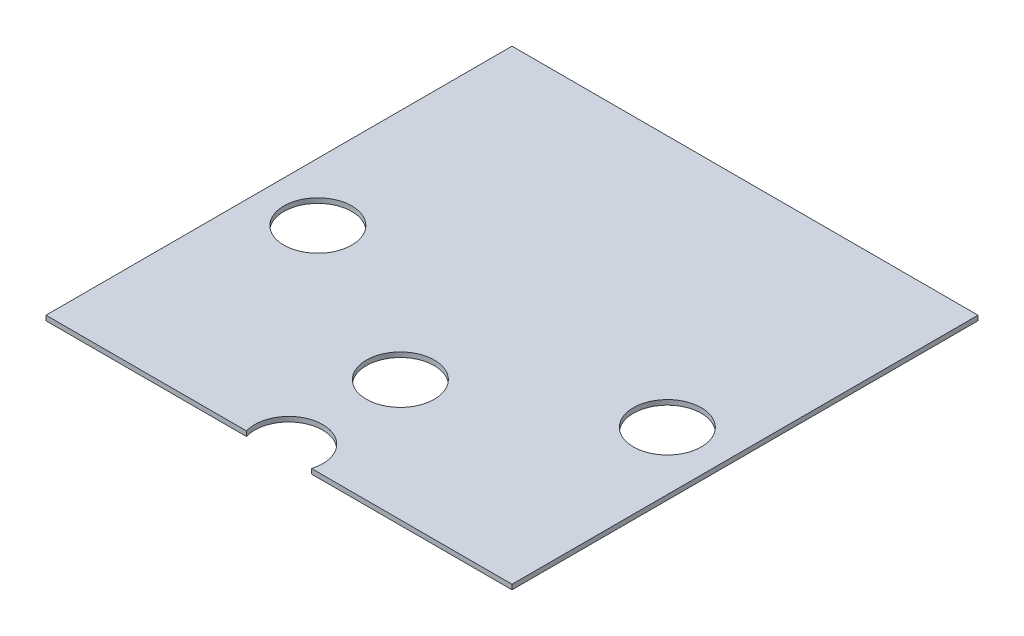
SolidWorks part; units mm, degrees
ref_plane "Front Plane" through (0, 0, 0) normal (0, 0, 1) x (1, 0, 0)
ref_plane "Top Plane" through (0, 0, 0) normal (0, 1, 0) x (1, 0, 0)
ref_plane "Right Plane" through (0, 0, 0) normal (1, 0, 0) x (0, 0, -1)
sketch "Sketch1" plane through (0, 0, 0) normal (0, 1, 0) x (1, 0, 0)
  line L1 (-387.1576, 281.7091) -> (222.4424, 281.7091)
  line L2 (-387.1576, 281.7091) -> (-387.1576, -327.8909)
  line L3 (-387.1576, -327.8909) -> (222.4424, -327.8909)
  line L4 (222.4424, 281.7091) -> (222.4424, -327.8909)
  dimension "D1" = 609.6
  dimension "D2" = 609.6
extrude "Boss-Extrude1" add sketch "Sketch1" along normal blind 6.35
sketch "Sketch2" plane through (0, 6.35, 0) normal (0, 1, 0) x (1, 0, 0)
  line L12 (82.7424, -547.9486) -> (82.7424, -311.0332)
  line L14 (89.0924, -549.9737) -> (89.0924, -309.0081)
  line L18 (-355.4076, -429.4909) -> (-361.7576, -429.4909)
  line L19 (197.0424, -429.4909) -> (190.6924, -429.4909)
  circle A5 centre (-82.3576, -296.1409) radius 63.5
  circle A9 centre (-82.3576, -296.1409) radius 69.85
  circle A13 centre (-82.3576, -448.5409) radius 82.55
  circle A17 centre (146.2424, -48.4909) radius 50.8
  circle A21 centre (-82.3576, -588.2409) radius 44.45
  circle A25 centre (-82.3576, -150.0909) radius 63.5
  circle A29 centre (-82.3576, -169.1409) radius 44.45
  circle A33 centre (-82.3576, -315.1909) radius 44.45
  circle A37 centre (-82.3576, -480.2909) radius 44.45
  circle A143 centre (-82.3576, -150.0909) radius 69.85
  circle A145 centre (-82.3576, -448.5409) radius 76.2
  circle A147 centre (-82.3576, -721.5909) radius 44.45
  circle A149 centre (-310.9576, -48.4909) radius 44.45
  circle A151 centre (146.2424, -48.4909) radius 44.45
  circle A153 centre (-310.9576, -48.4909) radius 50.8
  arc A155 (82.7424, -311.0332) -> (82.7424, -547.9486) centre (-82.3576, -429.4909) ccw
  arc A157 (89.0924, -309.0081) -> (89.0924, -549.9737) centre (-82.3576, -429.4909) ccw
  ellipse E2 centre (-82.3576, -429.4909) end of major axis (-82.3576, -226.2909) minor radius 177.8
  ellipse E4 centre (-82.3576, -429.4909) end of major axis (-82.3576, -92.9409) minor radius 273.05 (-355.4076, -429.4909) -> (190.6924, -429.4909) ccw
  spline S2 degree 3 poles (-361.7576, -429.4909) (-361.7576, -440.6643) (-360.866, -463.0413) (-355.5354, -507.3399) (-342.2995, -561.1377) (-316.4719, -620.7036) (-281.6498, -673.014) (-239.1144, -716.0513) (-190.4497, -748.1229) (-137.5067, -767.9257) (-82.3576, -774.6235) (-27.2084, -767.9257) (25.7346, -748.1229) (74.3993, -716.0513) (116.9346, -673.014) (151.7568, -620.7036) (177.5843, -561.1377) (190.8203, -507.3399) (196.1509, -463.0413) (197.0424, -440.6643) (197.0424, -429.4909) knots 1.570796 1.570796 1.570796 1.570796 1.668971 1.767146 1.963495 2.159845 2.356194 2.552544 2.748894 2.945243 3.141593 3.337942 3.534292 3.730641 3.926991 4.12334 4.31969 4.516039 4.614214 4.712389 4.712389 4.712389 4.712389
extrude "Cut-Extrude1" cut sketch "Sketch2" against normal blind 101.6
